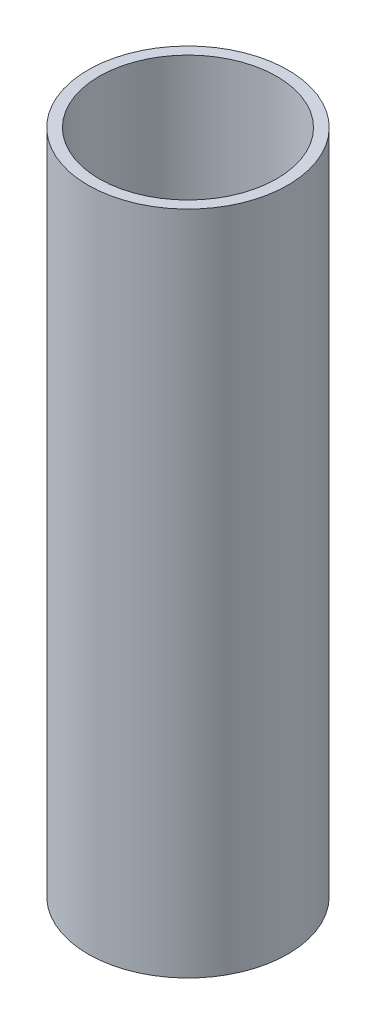
SolidWorks part; units mm, degrees
material "Thornel Mat VMA"
ref_plane "前视基准面" through (0, 0, 0) normal (0, 0, 1) x (1, 0, 0)
ref_plane "上视基准面" through (0, 0, 0) normal (0, 1, 0) x (1, 0, 0)
ref_plane "右视基准面" through (0, 0, 0) normal (1, 0, 0) x (0, 0, -1)
sketch "草图1" plane through (0, 0, 0) normal (0, 1, 0) x (1, 0, 0)
  circle A0 centre (0, 0) radius 9
  circle A1 centre (0, 0) radius 8
  dimension "D1" = 18
  dimension "D2" = 1
extrude "凸台-拉伸2" add sketch "草图1" along normal blind 60
